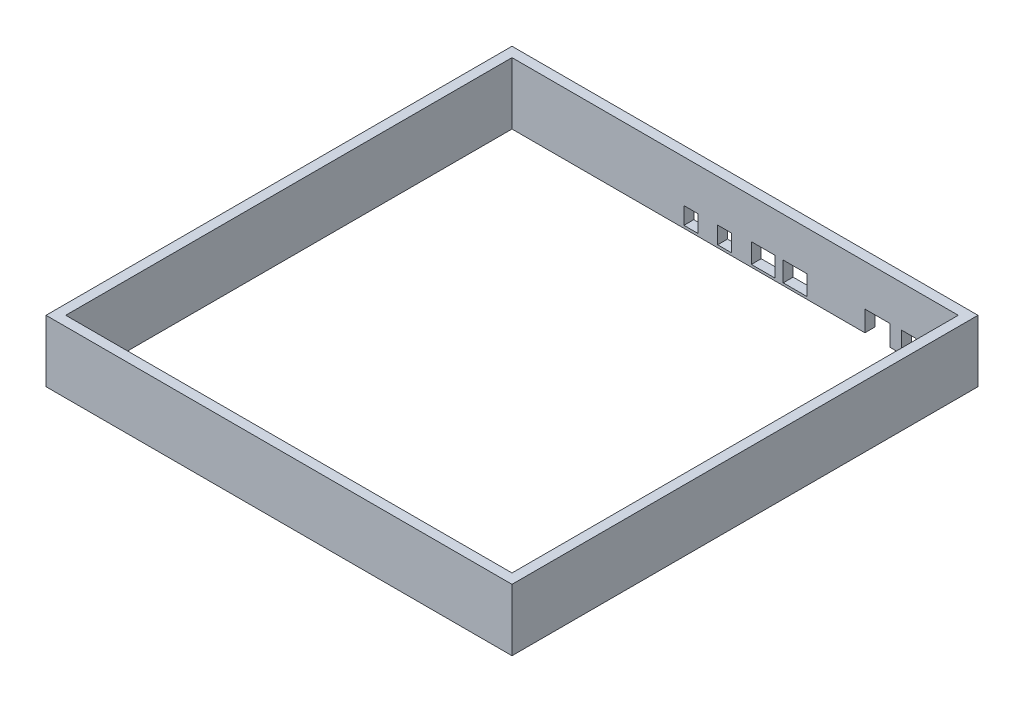
SolidWorks part; units mm, degrees
ref_plane "Front Plane" through (0, 0, 0) normal (0, 0, 1) x (1, 0, 0)
ref_plane "Top Plane" through (0, 0, 0) normal (0, 1, 0) x (1, 0, 0)
ref_plane "Right Plane" through (0, 0, 0) normal (1, 0, 0) x (0, 0, -1)
sketch "Sketch1" plane through (0, 0, 0) normal (0, 1, 0) x (1, 0, 0)
  line L1 (-150, -150) -> (150, -150)
  line L2 (-150, -150) -> (-150, 150)
  line L3 (-150, 150) -> (150, 150)
  line L4 (150, -150) -> (150, 150)
  line L5 (-150, -150) -> (150, 150) construction
  line L6 (-150, 150) -> (150, -150) construction
  line L7 (-143.65, -143.65) -> (143.65, -143.65)
  line L8 (-143.65, -143.65) -> (-143.65, 143.65)
  line L9 (-143.65, 143.65) -> (143.65, 143.65)
  line L10 (143.65, -143.65) -> (143.65, 143.65)
  line L11 (-143.65, -143.65) -> (143.65, 143.65) construction
  line L12 (-143.65, 143.65) -> (143.65, -143.65) construction
  point P0 (0, 0)
  point P6 (0, 0)
  dimension "D1" = 300
  dimension "D2" = 300
  dimension "D3" = 6.35
extrude "Boss-Extrude1" add sketch "Sketch1" along normal blind 39.8272
sketch "Sketch3" plane through (0, 0, -150) normal (0, 0, -1) x (-1, 0, 0)
  line L0 (-83.5466, -0.0762) -> (-99.5486, -0.0762) construction
  line L1 (-116.5666, 2.2408) -> (-107.152, 2.2408)
  line L2 (-116.5666, 2.2408) -> (-116.5666, 13.306)
  line L3 (-116.5666, 13.306) -> (-107.152, 13.306)
  line L4 (-107.152, 2.2408) -> (-107.152, 13.306)
  line L5 (-99.5486, 13.2588) -> (-83.5466, 13.2588)
  line L6 (-99.5486, 13.2588) -> (-99.5486, -0.0762)
  line L7 (-99.5486, -0.0762) -> (-83.5466, -0.0762)
  line L8 (-83.5466, 13.2588) -> (-83.5466, -0.0762)
  line L9 (-83.5466, -0.0762) -> (-83.5466, 13.2588) construction
  line L11 (-46.2684, 14.2748) -> (-30.9684, 14.2748)
  line L12 (-46.2684, 14.2748) -> (-46.2684, 1.5748)
  line L13 (-46.2684, 1.5748) -> (-30.9684, 1.5748)
  line L14 (-30.9684, 14.2748) -> (-30.9684, 1.5748)
  line L15 (-25.7426, 14.2748) -> (-10.4426, 14.2748)
  line L16 (-25.7426, 14.2748) -> (-25.7426, 1.5748)
  line L17 (-25.7426, 1.5748) -> (-10.4426, 1.5748)
  line L18 (-10.4426, 14.2748) -> (-10.4426, 1.5748)
  line L23 (11.2574, 1.6748) -> (11.2574, 12.6748) construction
  line L24 (2.2574, 1.6748) -> (11.2574, 1.6748)
  line L25 (2.2574, 1.6748) -> (2.2574, 12.6748)
  line L30 (2.2574, 12.6748) -> (11.2574, 12.6748)
  line L31 (26.9415, 10.936) -> (28.4574, 8.1748) construction
  line L32 (11.2574, 1.6748) -> (11.2574, 12.6748)
  line L34 (23.9574, 12.6748) -> (32.9574, 12.6748)
  line L35 (23.9574, 12.6748) -> (23.9574, 1.6748)
  line L36 (23.9574, 1.6748) -> (32.9574, 1.6748)
  line L37 (32.9574, 12.6748) -> (32.9574, 1.6748)
  circle A3 centre (28.4574, 8.1748) radius 3.15 construction
  arc A4 (26.9415, 10.936) -> (26.9415, 5.4136) centre (28.4574, 8.1748) ccw
extrude "Cut-Extrude1" cut sketch "Sketch3" against normal up to next
